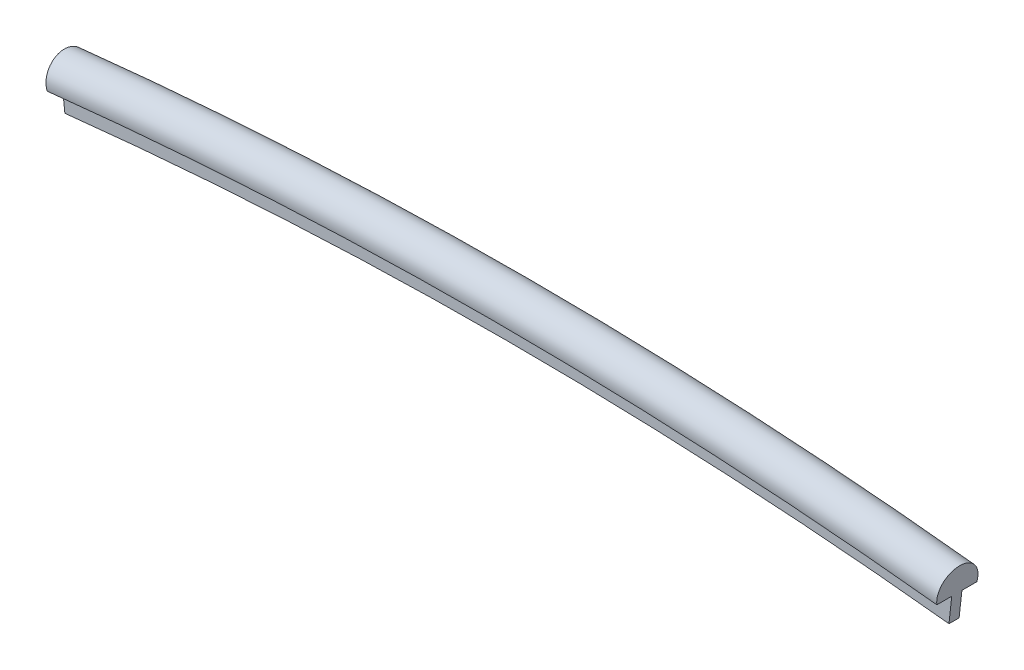
SolidWorks part; units mm, degrees
ref_plane "Front Plane" through (0, 0, 0) normal (0, 0, 1) x (1, 0, 0)
ref_plane "Top Plane" through (0, 0, 0) normal (0, 1, 0) x (1, 0, 0)
ref_plane "Right Plane" through (0, 0, 0) normal (1, 0, 0) x (0, 0, -1)
sketch "Sketch2" plane through (0, 0, 0) normal (1, 0, 0) x (0, 0, -1)
  line L0 (0, 241.3) -> (0, 0) construction
  line L2 (0, 241.3) -> (0, 239.8) construction
  line L3 (0, 239.8) -> (0.3, 239.8)
  line L4 (0, 239.8) -> (-0.3, 239.8)
  line L5 (-0.3, 239.8) -> (-0.3, 241.3)
  line L6 (0.3, 239.8) -> (0.3, 241.3)
  line L7 (0, 241.3) -> (0, 242.8) construction
  line L8 (-1.18, 241.3) -> (-0.3, 241.3)
  line L9 (0.3, 241.3) -> (1.18, 241.3)
  arc A0 (-1.18, 241.3) -> (1.18, 241.3) centre (0, 241.586) cw
  point P14 (0, 241.3)
ref_axis "Axis2" through (0, 0, 70.5976) along (0, 0, -1)
revolve "Revolve1" add sketch "Sketch2" angle 6.257 about axis through (0, 0, 70.5976) along (0, 0, -1)
